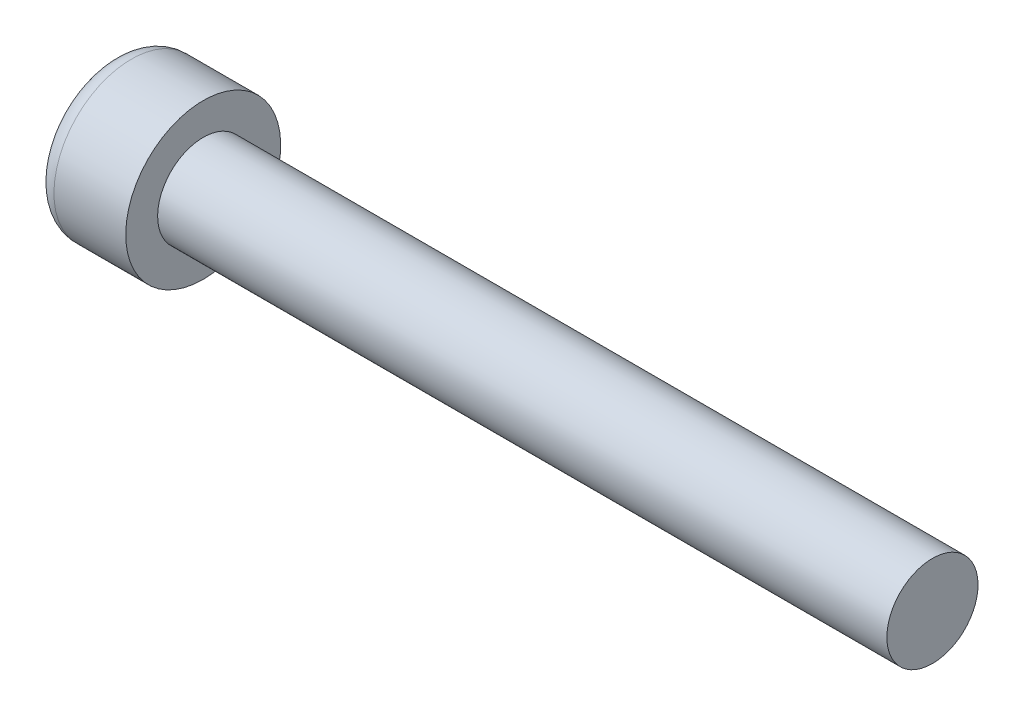
SolidWorks part; units mm, degrees
material "Plain Carbon Steel"
ref_plane "Front Plane" through (0, 0, 0) normal (0, 0, 1) x (1, 0, 0)
ref_plane "Top Plane" through (0, 0, 0) normal (0, 1, 0) x (1, 0, 0)
ref_plane "Right Plane" through (0, 0, 0) normal (1, 0, 0) x (0, 0, -1)
sketch "Sketch1" plane through (0, 0, 0) normal (0, 0, 1) x (1, 0, 0)
  line L0 (0, 0) -> (0, 3.1875)
  line L1 (1.0625, 4.25) -> (5, 4.25)
  line L2 (5, 4.25) -> (5, 2.5)
  line L3 (5, 2.5) -> (45, 2.5)
  line L4 (45, 2.5) -> (45, 0)
  line L5 (45, 0) -> (0, 0) construction
  line L6 (1.0625, 3.1875) -> (1.0625, 2.125) construction
  line L7 (1.0625, 2.125) -> (1.0625, 1.0625) construction
  line L8 (1.0625, 1.0625) -> (1.0625, 0) construction
  line L9 (1.0625, 4.25) -> (1.0625, 3.1875) construction
  line L10 (0, 0) -> (45, 0)
  arc A0 (0, 3.1875) -> (1.0625, 4.25) centre (1.0625, 3.1875) cw
  dimension "D1" = 5
  dimension "D2" = 8.5
  dimension "D3" = 5
  dimension "D4" = 40
revolve "Revolve1" add sketch "Sketch1" angle 360 about L10
sketch "Sketch2" plane through (0, 0, 0) normal (-1, 0, 0) x (0, 0, 1)
  line L1 (0, 2.3094) -> (-2, 1.1547)
  line L2 (-2, 1.1547) -> (-2, -1.1547)
  line L3 (-2, -1.1547) -> (0, -2.3094)
  line L4 (0, -2.3094) -> (2, -1.1547)
  line L5 (2, -1.1547) -> (2, 1.1547)
  line L6 (2, 1.1547) -> (0, 2.3094)
  circle A0 centre (0, 0) radius 2 construction
  dimension "D1" = 4
extrude "Cut-Extrude1" cut sketch "Sketch2" against normal blind 2.5
